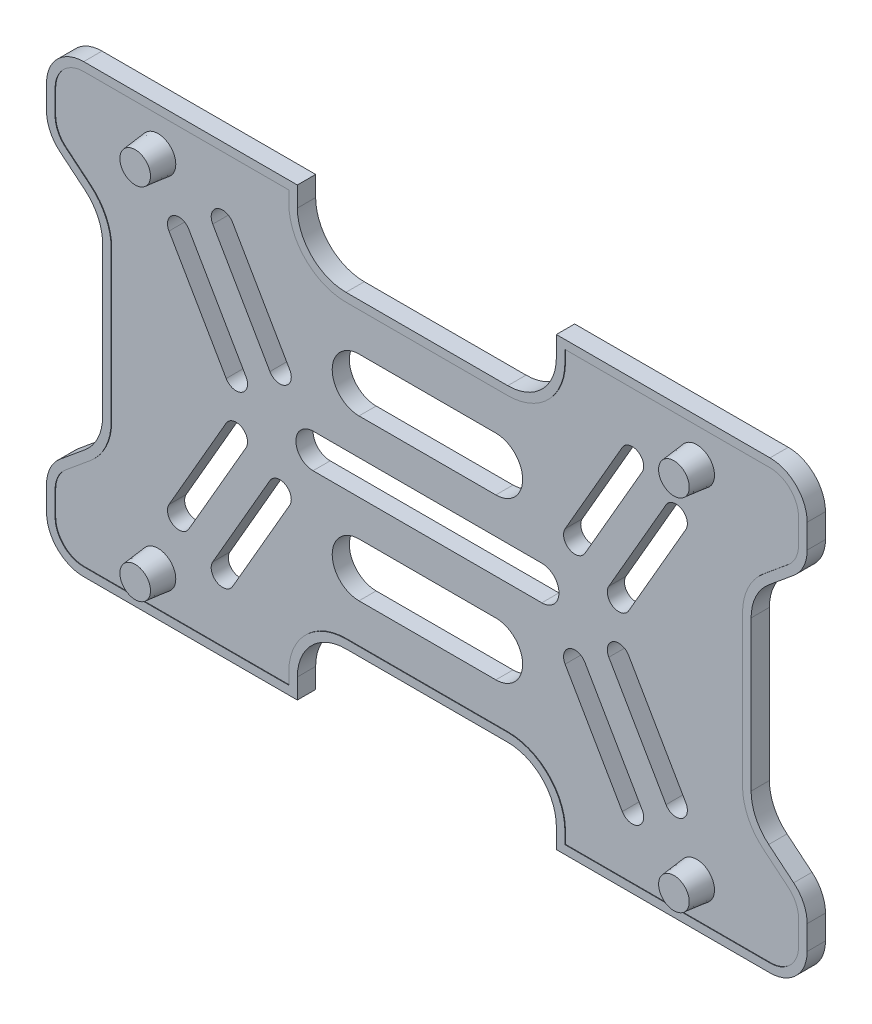
SolidWorks part; units mm, degrees
ref_plane "Front Plane" through (0, 0, 0) normal (0, 0, 1) x (1, 0, 0)
ref_plane "Top Plane" through (0, 0, 0) normal (0, 1, 0) x (1, 0, 0)
ref_plane "Right Plane" through (0, 0, 0) normal (1, 0, 0) x (0, 0, -1)
sketch "Sketch1" plane through (0, 0, 0) normal (0, 0, 1) x (1, 0, 0)
  line L0 (0, 0) -> (60.7869, 0) construction
  line L1 (65, -37.5) -> (-65, -37.5) construction
  line L2 (65, -37.5) -> (65, 37.5) construction
  line L3 (65, 37.5) -> (-65, 37.5) construction
  line L4 (-65, -37.5) -> (-65, 37.5) construction
  line L5 (65, -37.5) -> (-65, 37.5) construction
  line L6 (65, 37.5) -> (-65, -37.5) construction
  line L7 (0, 0) -> (0, 49.3998) construction
  line L11 (-53, 37.5) -> (-30.5, 37.5)
  line L12 (53, 37.5) -> (60, 37.5)
  line L13 (65, 32.5) -> (65, 28.2834)
  line L14 (63.1897, 24.433) -> (58.8206, 20.8135)
  line L15 (55.2, 13.1127) -> (55.2, -13.1127)
  line L16 (30.5, 37.5) -> (24.142, 37.5)
  line L17 (24.142, 37.5) -> (24.142, 35.5)
  line L18 (14.142, 25.5) -> (-14.142, 25.5)
  line L19 (-55.2, 13.1127) -> (-55.2, -13.1127)
  line L20 (-63.1897, 24.433) -> (-58.8206, 20.8135)
  line L21 (-65, 32.5) -> (-65, 28.2834)
  line L22 (-53, 37.5) -> (-60, 37.5)
  line L26 (-24.142, 37.5) -> (-24.142, 35.5)
  line L27 (-30.5, 37.5) -> (-24.142, 37.5)
  line L28 (-30.5, -37.5) -> (-24.142, -37.5)
  line L29 (-24.142, -37.5) -> (-24.142, -35.5)
  line L33 (-53, -37.5) -> (-60, -37.5)
  line L34 (-65, -32.5) -> (-65, -28.2834)
  line L35 (-63.1897, -24.433) -> (-58.8206, -20.8135)
  line L36 (14.142, -25.5) -> (-14.142, -25.5)
  line L37 (24.142, -37.5) -> (24.142, -35.5)
  line L38 (30.5, -37.5) -> (24.142, -37.5)
  line L39 (63.1897, -24.433) -> (58.8206, -20.8135)
  line L40 (65, -32.5) -> (65, -28.2834)
  line L41 (53, -37.5) -> (60, -37.5)
  line L45 (53, 37.5) -> (30.5, 37.5)
  line L46 (53, -37.5) -> (30.5, -37.5)
  line L47 (-53, -37.5) -> (-30.5, -37.5)
  arc A2 (65, 28.2834) -> (63.1897, 24.433) centre (60, 28.2834) cw
  arc A3 (60, 37.5) -> (65, 32.5) centre (60, 32.5) cw
  arc A4 (24.142, 35.5) -> (14.142, 25.5) centre (14.142, 35.5) cw
  arc A5 (58.8206, 20.8135) -> (55.2, 13.1127) centre (65.2, 13.1127) ccw
  arc A6 (-58.8206, 20.8135) -> (-55.2, 13.1127) centre (-65.2, 13.1127) cw
  arc A7 (-65, 28.2834) -> (-63.1897, 24.433) centre (-60, 28.2834) ccw
  arc A8 (-60, 37.5) -> (-65, 32.5) centre (-60, 32.5) ccw
  arc A10 (-24.142, 35.5) -> (-14.142, 25.5) centre (-14.142, 35.5) ccw
  arc A11 (-24.142, -35.5) -> (-14.142, -25.5) centre (-14.142, -35.5) cw
  arc A13 (-60, -37.5) -> (-65, -32.5) centre (-60, -32.5) cw
  arc A14 (-65, -28.2834) -> (-63.1897, -24.433) centre (-60, -28.2834) cw
  arc A15 (-58.8206, -20.8135) -> (-55.2, -13.1127) centre (-65.2, -13.1127) ccw
  arc A16 (58.8206, -20.8135) -> (55.2, -13.1127) centre (65.2, -13.1127) cw
  arc A17 (24.142, -35.5) -> (14.142, -25.5) centre (14.142, -35.5) ccw
  arc A18 (60, -37.5) -> (65, -32.5) centre (60, -32.5) ccw
  arc A19 (65, -28.2834) -> (63.1897, -24.433) centre (60, -28.2834) ccw
  circle A24 centre (-47.1, 31.4) radius 3.1 construction
  circle A25 centre (47.1, 31.4) radius 3.1 construction
  circle A26 centre (47.1, -31.4) radius 3.1 construction
  circle A27 centre (-47.1, -31.4) radius 3.1 construction
  point P0 (0, 0)
  point P11 (55.2, 31.4)
  point P29 (65, 25.9326)
  point P57 (0, 25.5)
  point P58 (55.2, 0)
  point P59 (-55.2, 0)
  point P101 (-47.1, 31.4)
  dimension "D9" = 5
  dimension "D10" = 10
  dimension "D12" = 6.2
  dimension "D1" = 130
  dimension "D2" = 75
  dimension "D7" = 12
extrude "Boss-Extrude1" add sketch "Sketch1" along normal mid plane 3
ref_plane "Plane1" through (0, 0, 0) normal (0, 1, 0) x (1, 0, 0)
ref_plane "Plane2" through (0, 0, 0) normal (1, 0, 0) x (0, 0, -1)
sketch "Sketch2" plane through (0, 0, 1.5) normal (0, 0, 1) x (1, 0, 0)
  circle A0 centre (47.1, -31.4) radius 3.1 construction
  circle A1 centre (47.1, 31.4) radius 3.1 construction
  circle A2 centre (-47.1, -31.4) radius 3.1 construction
  circle A3 centre (-47.1, 31.4) radius 3.1 construction
  circle A4 centre (47.1, -31.4) radius 3.1
  circle A5 centre (47.1, 31.4) radius 3.1
  circle A6 centre (-47.1, -31.4) radius 3.1
  circle A7 centre (-47.1, 31.4) radius 3.1
extrude "Boss-Extrude2" add sketch "Sketch2" along normal blind 4 draft 6
sketch "Sketch3" plane through (0, 0, 1.5) normal (0, 0, 1) x (1, 0, 0)
  line L0 (0, 0) -> (-45.2641, 0) construction
  line L1 (0, 0) -> (0, 15.3482) construction
  line L2 (-20, 0) -> (20, 0) construction
  line L3 (-20, 3) -> (20, 3)
  line L4 (-20, -3) -> (20, -3)
  line L5 (-30.9267, 0) -> (-41.9821, 19.1484) construction
  line L6 (-20.4642, 0) -> (-32.9323, 21.5953) construction
  line L7 (-43.4542, 21.6982) -> (-33.4542, 4.3777) construction
  line L8 (-41.7222, 22.6982) -> (-31.7222, 5.3777)
  line L9 (-45.1863, 20.6982) -> (-35.1863, 3.3777)
  line L10 (-25.8068, 9.2535) -> (-35.8068, 26.5741) construction
  line L11 (-27.5388, 8.2535) -> (-37.5388, 25.5741)
  line L12 (-24.0747, 10.2535) -> (-34.0747, 27.5741)
  line L13 (43.4542, 21.6982) -> (33.4542, 4.3777) construction
  line L14 (41.7222, 22.6982) -> (31.7222, 5.3777)
  line L15 (45.1863, 20.6982) -> (35.1863, 3.3777)
  line L16 (25.8068, 9.2535) -> (35.8068, 26.5741) construction
  line L17 (27.5388, 8.2535) -> (37.5388, 25.5741)
  line L18 (24.0747, 10.2535) -> (34.0747, 27.5741)
  line L19 (43.4542, -21.6982) -> (33.4542, -4.3777) construction
  line L20 (41.7222, -22.6982) -> (31.7222, -5.3777)
  line L21 (45.1863, -20.6982) -> (35.1863, -3.3777)
  line L22 (25.8068, -9.2535) -> (35.8068, -26.5741) construction
  line L23 (27.5388, -8.2535) -> (37.5388, -25.5741)
  line L24 (24.0747, -10.2535) -> (34.0747, -27.5741)
  line L25 (-43.4542, -21.6982) -> (-33.4542, -4.3777) construction
  line L26 (-41.7222, -22.6982) -> (-31.7222, -5.3777)
  line L27 (-45.1863, -20.6982) -> (-35.1863, -3.3777)
  line L28 (-25.8068, -9.2535) -> (-35.8068, -26.5741) construction
  line L29 (-27.5388, -8.2535) -> (-37.5388, -25.5741)
  line L30 (-24.0747, -10.2535) -> (-34.0747, -27.5741)
  line L31 (-11.9664, 14) -> (11.9664, 14) construction
  line L32 (-11.9664, 18.6825) -> (11.9664, 18.6825)
  line L33 (-11.9664, 9.3175) -> (11.9664, 9.3175)
  line L34 (-11.9664, -14) -> (11.9664, -14) construction
  line L35 (-11.9664, -18.6825) -> (11.9664, -18.6825)
  line L36 (-11.9664, -9.3175) -> (11.9664, -9.3175)
  arc A0 (-20, 3) -> (-20, -3) centre (-20, 0) ccw
  arc A1 (20, -3) -> (20, 3) centre (20, 0) ccw
  arc A2 (-41.7222, 22.6982) -> (-45.1863, 20.6982) centre (-43.4542, 21.6982) ccw
  arc A3 (-35.1863, 3.3777) -> (-31.7222, 5.3777) centre (-33.4542, 4.3777) ccw
  arc A4 (-27.5388, 8.2535) -> (-24.0747, 10.2535) centre (-25.8068, 9.2535) ccw
  arc A5 (-34.0747, 27.5741) -> (-37.5388, 25.5741) centre (-35.8068, 26.5741) ccw
  arc A6 (41.7222, 22.6982) -> (45.1863, 20.6982) centre (43.4542, 21.6982) cw
  arc A7 (35.1863, 3.3777) -> (31.7222, 5.3777) centre (33.4542, 4.3777) cw
  arc A8 (27.5388, 8.2535) -> (24.0747, 10.2535) centre (25.8068, 9.2535) cw
  arc A9 (34.0747, 27.5741) -> (37.5388, 25.5741) centre (35.8068, 26.5741) cw
  arc A10 (41.7222, -22.6982) -> (45.1863, -20.6982) centre (43.4542, -21.6982) ccw
  arc A11 (35.1863, -3.3777) -> (31.7222, -5.3777) centre (33.4542, -4.3777) ccw
  arc A12 (27.5388, -8.2535) -> (24.0747, -10.2535) centre (25.8068, -9.2535) ccw
  arc A13 (34.0747, -27.5741) -> (37.5388, -25.5741) centre (35.8068, -26.5741) ccw
  arc A14 (-41.7222, -22.6982) -> (-45.1863, -20.6982) centre (-43.4542, -21.6982) cw
  arc A15 (-35.1863, -3.3777) -> (-31.7222, -5.3777) centre (-33.4542, -4.3777) cw
  arc A16 (-27.5388, -8.2535) -> (-24.0747, -10.2535) centre (-25.8068, -9.2535) cw
  arc A17 (-34.0747, -27.5741) -> (-37.5388, -25.5741) centre (-35.8068, -26.5741) cw
  arc A18 (-11.9664, 18.6825) -> (-11.9664, 9.3175) centre (-11.9664, 14) ccw
  arc A19 (11.9664, 9.3175) -> (11.9664, 18.6825) centre (11.9664, 14) ccw
  arc A20 (-11.9664, -18.6825) -> (-11.9664, -9.3175) centre (-11.9664, -14) cw
  arc A21 (11.9664, -9.3175) -> (11.9664, -18.6825) centre (11.9664, -14) cw
  point P6 (0, 0)
  point P17 (-38.4542, 13.038)
  point P23 (-30.8068, 17.9138)
  point P31 (38.4542, 13.038)
  point P38 (30.8068, 17.9138)
  point P45 (38.4542, -13.038)
  point P52 (30.8068, -17.9138)
  point P59 (-38.4542, -13.038)
  point P66 (-30.8068, -17.9138)
  point P73 (0, 14)
  point P80 (0, -14)
  dimension "D1" = 40
  dimension "D2" = 6
  dimension "D3" = 120
  dimension "D4" = 20
  dimension "D5" = 4
  dimension "D6" = 14
extrude "Cut-Extrude1" cut sketch "Sketch3" against normal through all
sketch "Sketch4" plane through (0, 0, 1.5) normal (0, 0, 1) x (1, 0, 0)
  line L40 (60, 37.5) -> (24.142, 37.5)
  line L41 (24.142, 37.5) -> (24.142, 35.5)
  line L42 (14.142, 25.5) -> (-14.142, 25.5)
  line L43 (-24.142, 35.5) -> (-24.142, 37.5)
  line L44 (-24.142, 37.5) -> (-60, 37.5)
  line L45 (-65, 32.5) -> (-65, 28.2834)
  line L46 (-63.1897, 24.433) -> (-58.8206, 20.8135)
  line L47 (-55.2, 13.1127) -> (-55.2, -13.1127)
  line L48 (-58.8206, -20.8135) -> (-63.1897, -24.433)
  line L49 (-65, -28.2834) -> (-65, -32.5)
  line L50 (-60, -37.5) -> (-24.142, -37.5)
  line L51 (-24.142, -37.5) -> (-24.142, -35.5)
  line L52 (-14.142, -25.5) -> (14.142, -25.5)
  line L53 (24.142, -35.5) -> (24.142, -37.5)
  line L54 (24.142, -37.5) -> (60, -37.5)
  line L55 (65, -32.5) -> (65, -28.2834)
  line L56 (63.1897, -24.433) -> (58.8206, -20.8135)
  line L57 (55.2, -13.1127) -> (55.2, 13.1127)
  line L58 (58.8206, 20.8135) -> (63.1897, 24.433)
  line L59 (65, 28.2834) -> (65, 32.5)
  line L60 (60, 37.5) -> (24.142, 37.5)
  line L61 (24.142, 37.5) -> (24.142, 35.5)
  line L62 (14.142, 25.5) -> (-14.142, 25.5)
  line L63 (-24.142, 35.5) -> (-24.142, 37.5)
  line L64 (-24.142, 37.5) -> (-60, 37.5)
  line L65 (-65, 32.5) -> (-65, 28.2834)
  line L66 (-63.1897, 24.433) -> (-58.8206, 20.8135)
  line L67 (-55.2, 13.1127) -> (-55.2, -13.1127)
  line L68 (-58.8206, -20.8135) -> (-63.1897, -24.433)
  line L69 (-65, -28.2834) -> (-65, -32.5)
  line L70 (-60, -37.5) -> (-24.142, -37.5)
  line L71 (-24.142, -37.5) -> (-24.142, -35.5)
  line L72 (-14.142, -25.5) -> (14.142, -25.5)
  line L73 (24.142, -35.5) -> (24.142, -37.5)
  line L74 (24.142, -37.5) -> (60, -37.5)
  line L75 (65, -32.5) -> (65, -28.2834)
  line L76 (63.1897, -24.433) -> (58.8206, -20.8135)
  line L77 (55.2, -13.1127) -> (55.2, 13.1127)
  line L78 (58.8206, 20.8135) -> (63.1897, 24.433)
  line L79 (65, 28.2834) -> (65, 32.5)
  line L80 (60, 39) -> (22.642, 39)
  line L81 (22.642, 39) -> (22.642, 35.5)
  line L82 (14.142, 27) -> (-14.142, 27)
  line L83 (-22.642, 35.5) -> (-22.642, 39)
  line L84 (-22.642, 39) -> (-60, 39)
  line L85 (-66.5, 32.5) -> (-66.5, 28.2834)
  line L86 (-64.1466, 23.2778) -> (-59.7775, 19.6584)
  line L87 (-56.7, 13.1127) -> (-56.7, -13.1127)
  line L88 (-59.7775, -19.6584) -> (-64.1466, -23.2778)
  line L89 (-66.5, -28.2834) -> (-66.5, -32.5)
  line L90 (-60, -39) -> (-22.642, -39)
  line L91 (-22.642, -39) -> (-22.642, -35.5)
  line L92 (-14.142, -27) -> (14.142, -27)
  line L93 (22.642, -35.5) -> (22.642, -39)
  line L94 (22.642, -39) -> (60, -39)
  line L95 (66.5, -32.5) -> (66.5, -28.2834)
  line L96 (64.1466, -23.2778) -> (59.7775, -19.6584)
  line L97 (56.7, -13.1127) -> (56.7, 13.1127)
  line L98 (59.7775, 19.6584) -> (64.1466, 23.2778)
  line L99 (66.5, 28.2834) -> (66.5, 32.5)
  arc A32 (14.142, 25.5) -> (24.142, 35.5) centre (14.142, 35.5) ccw
  arc A33 (-24.142, 35.5) -> (-14.142, 25.5) centre (-14.142, 35.5) ccw
  arc A34 (-60, 37.5) -> (-65, 32.5) centre (-60, 32.5) ccw
  arc A35 (-65, 28.2834) -> (-63.1897, 24.433) centre (-60, 28.2834) ccw
  arc A36 (-55.2, 13.1127) -> (-58.8206, 20.8135) centre (-65.2, 13.1127) ccw
  arc A37 (-58.8206, -20.8135) -> (-55.2, -13.1127) centre (-65.2, -13.1127) ccw
  arc A38 (-63.1897, -24.433) -> (-65, -28.2834) centre (-60, -28.2834) ccw
  arc A39 (-65, -32.5) -> (-60, -37.5) centre (-60, -32.5) ccw
  arc A40 (-14.142, -25.5) -> (-24.142, -35.5) centre (-14.142, -35.5) ccw
  arc A41 (24.142, -35.5) -> (14.142, -25.5) centre (14.142, -35.5) ccw
  arc A42 (60, -37.5) -> (65, -32.5) centre (60, -32.5) ccw
  arc A43 (65, -28.2834) -> (63.1897, -24.433) centre (60, -28.2834) ccw
  arc A44 (55.2, -13.1127) -> (58.8206, -20.8135) centre (65.2, -13.1127) ccw
  arc A45 (58.8206, 20.8135) -> (55.2, 13.1127) centre (65.2, 13.1127) ccw
  arc A46 (63.1897, 24.433) -> (65, 28.2834) centre (60, 28.2834) ccw
  arc A47 (65, 32.5) -> (60, 37.5) centre (60, 32.5) ccw
  arc A48 (14.142, 25.5) -> (24.142, 35.5) centre (14.142, 35.5) ccw
  arc A49 (-24.142, 35.5) -> (-14.142, 25.5) centre (-14.142, 35.5) ccw
  arc A50 (-60, 37.5) -> (-65, 32.5) centre (-60, 32.5) ccw
  arc A51 (-65, 28.2834) -> (-63.1897, 24.433) centre (-60, 28.2834) ccw
  arc A52 (-55.2, 13.1127) -> (-58.8206, 20.8135) centre (-65.2, 13.1127) ccw
  arc A53 (-58.8206, -20.8135) -> (-55.2, -13.1127) centre (-65.2, -13.1127) ccw
  arc A54 (-63.1897, -24.433) -> (-65, -28.2834) centre (-60, -28.2834) ccw
  arc A55 (-65, -32.5) -> (-60, -37.5) centre (-60, -32.5) ccw
  arc A56 (-14.142, -25.5) -> (-24.142, -35.5) centre (-14.142, -35.5) ccw
  arc A57 (24.142, -35.5) -> (14.142, -25.5) centre (14.142, -35.5) ccw
  arc A58 (60, -37.5) -> (65, -32.5) centre (60, -32.5) ccw
  arc A59 (65, -28.2834) -> (63.1897, -24.433) centre (60, -28.2834) ccw
  arc A60 (55.2, -13.1127) -> (58.8206, -20.8135) centre (65.2, -13.1127) ccw
  arc A61 (58.8206, 20.8135) -> (55.2, 13.1127) centre (65.2, 13.1127) ccw
  arc A62 (63.1897, 24.433) -> (65, 28.2834) centre (60, 28.2834) ccw
  arc A63 (65, 32.5) -> (60, 37.5) centre (60, 32.5) ccw
  arc A64 (14.142, 27) -> (22.642, 35.5) centre (14.142, 35.5) ccw
  arc A65 (-22.642, 35.5) -> (-14.142, 27) centre (-14.142, 35.5) ccw
  arc A66 (-60, 39) -> (-66.5, 32.5) centre (-60, 32.5) ccw
  arc A67 (-66.5, 28.2834) -> (-64.1466, 23.2778) centre (-60, 28.2834) ccw
  arc A68 (-56.7, 13.1127) -> (-59.7775, 19.6584) centre (-65.2, 13.1127) ccw
  arc A69 (-59.7775, -19.6584) -> (-56.7, -13.1127) centre (-65.2, -13.1127) ccw
  arc A70 (-64.1466, -23.2778) -> (-66.5, -28.2834) centre (-60, -28.2834) ccw
  arc A71 (-66.5, -32.5) -> (-60, -39) centre (-60, -32.5) ccw
  arc A72 (-14.142, -27) -> (-22.642, -35.5) centre (-14.142, -35.5) ccw
  arc A73 (22.642, -35.5) -> (14.142, -27) centre (14.142, -35.5) ccw
  arc A74 (60, -39) -> (66.5, -32.5) centre (60, -32.5) ccw
  arc A75 (66.5, -28.2834) -> (64.1466, -23.2778) centre (60, -28.2834) ccw
  arc A76 (56.7, -13.1127) -> (59.7775, -19.6584) centre (65.2, -13.1127) ccw
  arc A77 (59.7775, 19.6584) -> (56.7, 13.1127) centre (65.2, 13.1127) ccw
  arc A78 (64.1466, 23.2778) -> (66.5, 28.2834) centre (60, 28.2834) ccw
  arc A79 (66.5, 32.5) -> (60, 39) centre (60, 32.5) ccw
  dimension "D1" = 0
  dimension "D2" = 1.5
extrude "Boss-Extrude5" add sketch "Sketch4" along normal blind 0.1 and the other way blind 3.1
